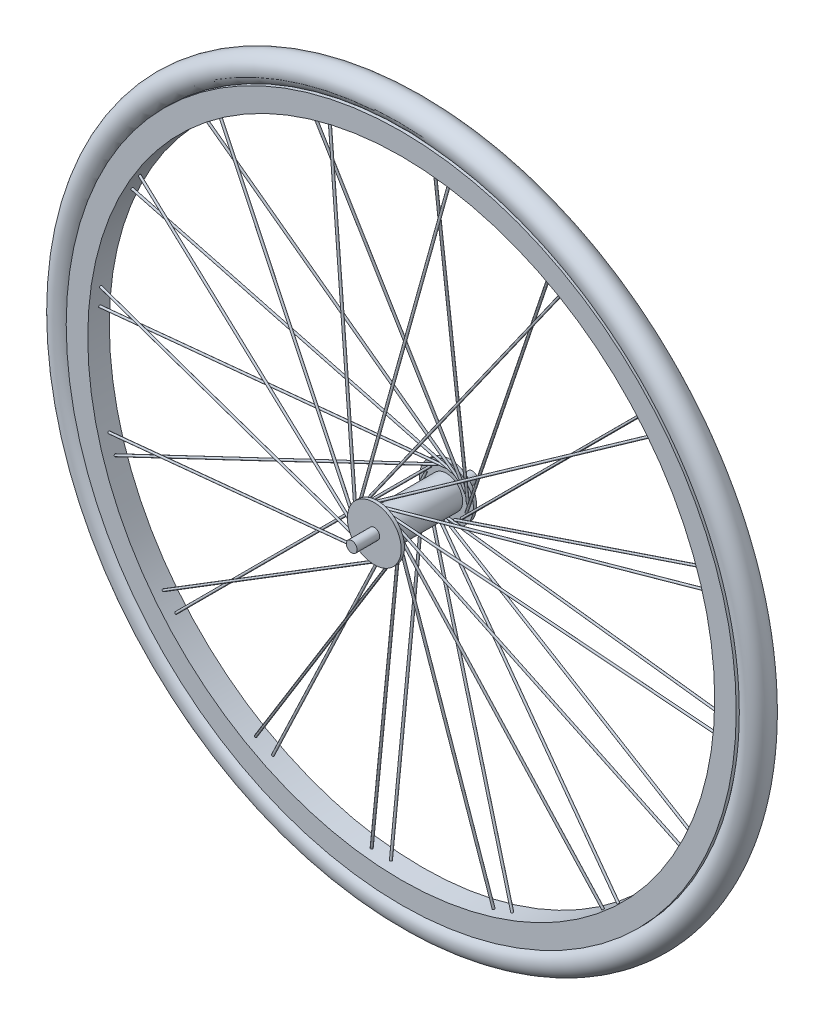
SolidWorks part; units mm, degrees
material "6061-T6 (SS)"
ref_plane "Alzado" through (0, 0, 0) normal (0, 0, 1) x (1, 0, 0)
ref_plane "Planta" through (0, 0, 0) normal (0, 1, 0) x (1, 0, 0)
ref_plane "Vista lateral" through (0, 0, 0) normal (1, 0, 0) x (0, 0, -1)
sketch "Sk_Eje" plane through (0, 0, 0) normal (0, 0, 1) x (1, 0, 0)
  circle A0 centre (0, 0) radius 5
  point P0 (0, 0)
  dimension "D1" = 10
extrude "Eje" add sketch "Sk_Eje" along normal blind 106 and the other way blind 6
sketch "Sk_Buje" plane through (0, 0, 0) normal (0, 0, 1) x (1, 0, 0)
  circle A0 centre (0, 0) radius 15
  point P0 (0, 0)
  dimension "D1" = 30
extrude "Buje" add sketch "Sk_Buje" along normal blind 70 from offset 15
sketch "Sk_Pestana_izq" plane through (0, 0, 0) normal (0, 0, 1) x (1, 0, 0)
  circle A0 centre (0, 0) radius 25
  point P0 (0, 0)
  dimension "D1" = 50
extrude "Pestana_izq" add sketch "Sk_Pestana_izq" along normal blind 3 from offset 15
sketch "Sk_Pestana_dcha" plane through (0, 0, 0) normal (0, 0, 1) x (1, 0, 0)
  circle A0 centre (0, 0) radius 25
  point P0 (0, 0)
  dimension "D1" = 50
extrude "Pestana_dcha" add sketch "Sk_Pestana_dcha" along normal blind 3 from offset 82
sketch "Sk_Llanta" plane through (0, 0, 0) normal (0, 0, 1) x (1, 0, 0)
  circle A0 centre (0, 0) radius 311
  circle A1 centre (0, 0) radius 291
  point P0 (0, 0)
  dimension "D1" = 622
  dimension "D2" = 582
extrude "Llanta" add sketch "Sk_Llanta" along normal blind 20 from offset 40
sketch "Sk_Cubierta" plane through (0, 0, 0) normal (0, 1, 0) x (1, 0, 0)
  line L0 (0, 950) -> (0, -1050) construction
  circle A0 centre (321.5, -50) radius 12.5
  point P0 (0, 0)
  dimension "D1" = 25
  dimension "D2" = 321.5
  dimension "D3" = 50
revolve "Cubierta" add sketch "Sk_Cubierta" angle 360 about L0
sketch3d "Eje_Radio_izq"
  line L0 (0, 20, 18) -> (-294.327, 20, 50)
  point P2 (-147.1635, 20, 34)
ref_plane "Plano_Radio_izq" through (-147.1635, 20, 34) normal (-0.9941, 0, 0.1081) x (0.1081, 0, 0.9941)
sketch "Sk_Radio_izq" plane through (-147.1635, 20, 34) normal (-0.9941, 0, 0.1081) x (0.1081, 0, 0.9941)
  circle A0 centre (0, 0) radius 1
extrude "Radio_izq" add sketch "Sk_Radio_izq" along normal mid plane 296.0615
sketch3d "Eje_Matriz_radios_izq"
  line L0 (0, 0, -500) -> (0, 0, 500)
pattern_circular "Matriz_radios_izq" count 16 over 360 about axis through (0, 0, 0) along (0, 0, 1) of "Radio_izq"
sketch3d "Eje_Radio_dcha"
  line L0 (3.902, 19.616, 82) -> (292.57, -37.805, 50)
  point P2 (148.236, -9.0945, 66)
ref_plane "Plano_Radio_dcha" through (148.236, -9.0945, 66) normal (0.975, -0.194, -0.1081) x (-0.106, 0.0211, -0.9941)
sketch "Sk_Radio_dcha" plane through (148.236, -9.0945, 66) normal (0.975, -0.194, -0.1081) x (-0.106, 0.0211, -0.9941)
  circle A0 centre (0, 0) radius 1
extrude "Radio_dcha" add sketch "Sk_Radio_dcha" along normal mid plane 296.0581
sketch3d "Eje_Matriz_radios_dcha"
  line L0 (0, 0, -500) -> (0, 0, 500)
pattern_circular "Matriz_radios_dcha" count 16 over 360 about axis through (0, 0, 0) along (0, 0, 1) of "Radio_dcha"
equation "\"diametro_cubierta\"= 668"
equation "\"longitud_eje\"= 100"
equation "\"ancho_buje\"= 70"
equation "\"diametro_llanta\"= 622"
